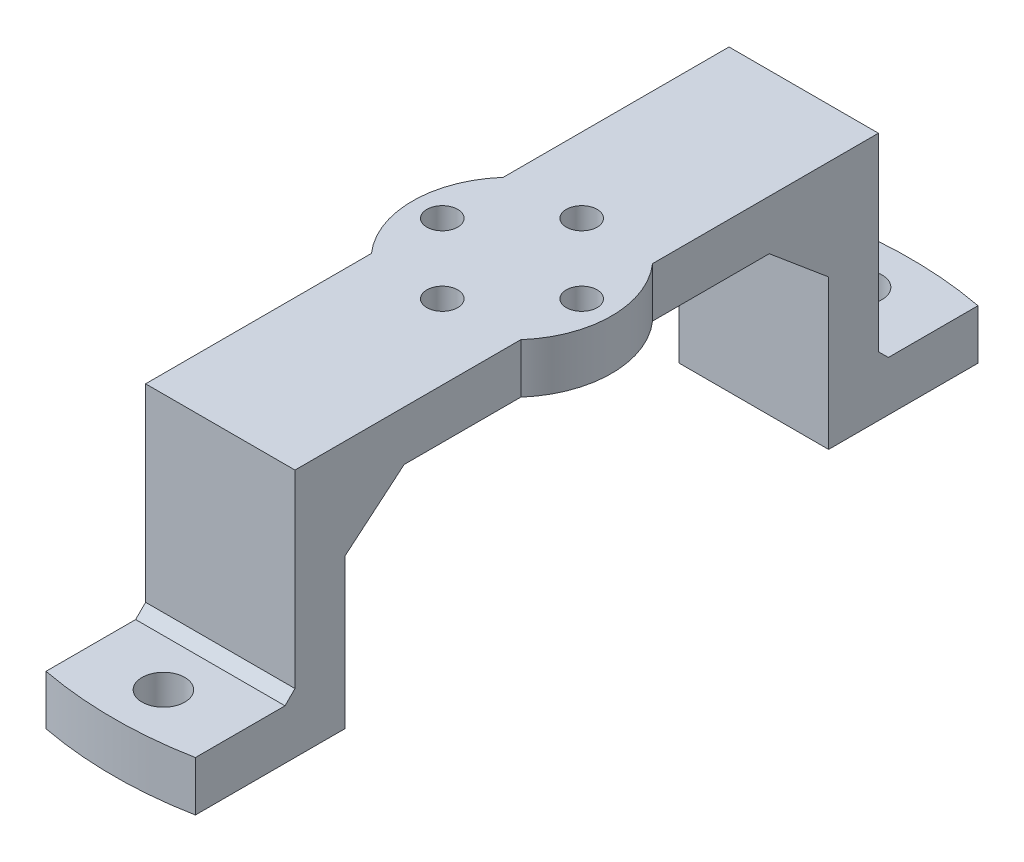
SolidWorks part; units mm, degrees
ref_plane "Front Plane" through (0, 0, 0) normal (0, 0, 1) x (1, 0, 0)
ref_plane "Top Plane" through (0, 0, 0) normal (0, 1, 0) x (1, 0, 0)
ref_plane "Right Plane" through (0, 0, 0) normal (1, 0, 0) x (0, 0, -1)
sketch "Sketch1" plane through (0, 0, 0) normal (0, 1, 0) x (1, 0, 0)
  line L0 (-7.5, -24.2906) -> (-7.5, -39.2906)
  line L2 (-7.5, 39.2906) -> (-7.5, 24.2906)
  line L4 (7.5, 39.2906) -> (7.5, 24.2906)
  line L5 (-7.5, 39.2906) -> (7.5, -39.2906) construction
  line L6 (-7.5, -39.2906) -> (7.5, 39.2906) construction
  line L7 (-7.5, -24.2906) -> (7.5, -24.2906)
  line L9 (-7.5, 24.2906) -> (7.5, 24.2906)
  line L11 (-7.5, -24.2906) -> (7.5, 24.2906) construction
  line L12 (-7.5, 24.2906) -> (7.5, -24.2906) construction
  line L13 (7.5, -24.2906) -> (7.5, -39.2906)
  arc A0 (7.5, 39.2906) -> (-7.5, 39.2906) centre (0, 0) ccw
  circle A1 centre (0, 0) radius 35 construction
  circle A2 centre (0, 35) radius 2.15
  circle A3 centre (0, -35) radius 2.15
  arc A4 (-7.5, -39.2906) -> (7.5, -39.2906) centre (0, 0) ccw
  dimension "D1" = 80
  dimension "D2" = 70
  dimension "D3" = 4.3
  dimension "D4" = 15
  dimension "D5" = 15
extrude "Boss-Extrude1" add sketch "Sketch1" along normal blind 5
sketch "Sketch2" plane through (0, 5, 0) normal (0, 1, 0) x (1, 0, 0)
  line L0 (7.5, -39.2906) -> (7.5, -24.2906) construction
  line L1 (-7.5, -24.2906) -> (7.5, -24.2906)
  line L2 (-7.5, -24.2906) -> (-7.5, -29.2906)
  line L3 (-7.5, -29.2906) -> (7.5, -29.2906)
  line L4 (7.5, -24.2906) -> (7.5, -29.2906)
  line L5 (7.5, 24.2906) -> (7.5, 39.2906) construction
  line L6 (-7.5, 24.2906) -> (7.5, 24.2906)
  line L7 (-7.5, 24.2906) -> (-7.5, 29.2906)
  line L8 (-7.5, 29.2906) -> (7.5, 29.2906)
  line L9 (7.5, 24.2906) -> (7.5, 29.2906)
  dimension "D1" = 5
  dimension "D2" = 5
extrude "Boss-Extrude2" add sketch "Sketch2" along normal blind 15
sketch "Sketch3" plane through (0, 20, 0) normal (0, 1, 0) x (1, 0, 0)
  line L1 (-7.5, -29.2906) -> (7.5, -29.2906)
  line L2 (-7.5, -29.2906) -> (-7.5, 29.2906)
  line L3 (-7.5, 29.2906) -> (7.5, 29.2906)
  line L4 (7.5, -29.2906) -> (7.5, 29.2906)
extrude "Boss-Extrude3" add sketch "Sketch3" along normal blind 5
sketch "Sketch4" plane through (0, 25, 0) normal (0, 1, 0) x (1, 0, 0)
  circle A0 centre (0, 0) radius 7 construction
  circle A2 centre (0, 0) radius 10
  dimension "D1" = 14
  dimension "D2" = 20
extrude "Boss-Extrude4" add sketch "Sketch4" against normal blind 5
sketch "Sketch5" plane through (0, 25, 0) normal (0, 1, 0) x (1, 0, 0)
  circle A0 centre (0, 0) radius 7 construction
  circle A1 centre (0, 7) radius 1.55
  circle A2 centre (7, 0) radius 1.55
  circle A3 centre (0, -7) radius 1.55
  circle A4 centre (-7, 0) radius 1.55
  dimension "D1" = 14
  dimension "D2" = 3.1
extrude "Cut-Extrude1" cut sketch "Sketch5" against normal blind 5
chamfer "Chamfer2" distance 5 angle 50 2 edges at (0, 20, -24.2906) (0, 20, 24.2906)
chamfer "Chamfer3" distance 1 angle 45 2 edges at (0, 5, -29.2906) (0, 5, 29.2906)
